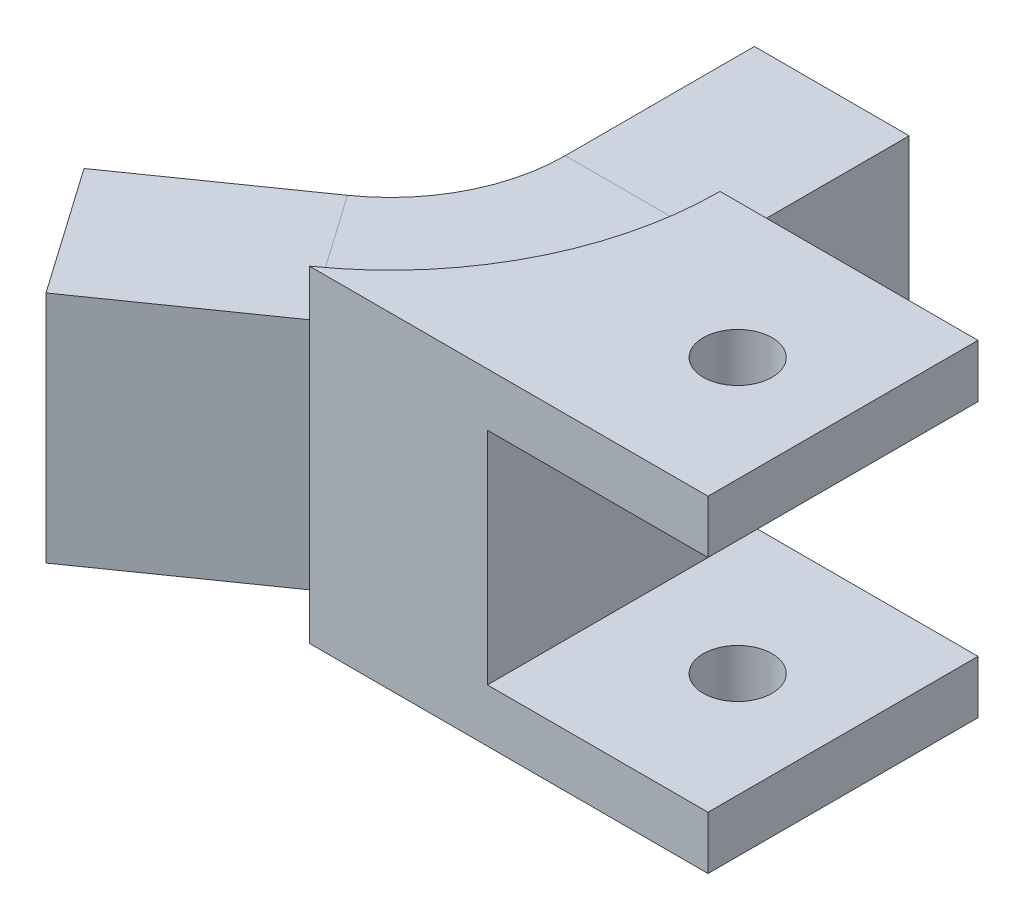
SolidWorks part; units mm, degrees
ref_plane "Front Plane" through (0, 0, 0) normal (0, 0, 1) x (1, 0, 0)
ref_plane "Top Plane" through (0, 0, 0) normal (0, 1, 0) x (1, 0, 0)
ref_plane "Right Plane" through (0, 0, 0) normal (1, 0, 0) x (0, 0, -1)
sketch "Sketch1" plane through (0, 0, 0) normal (0, 1, 0) x (1, 0, 0)
  line L0 (6.5349, -23.4717) -> (21.2796, -13.1473) construction
  line L1 (21.2796, -13.1473) -> (21.2796, 4.8527) construction
  line L2 (21.2796, 4.8527) -> (21.2796, 26.8527)
  line L3 (6.5349, -23.4717) -> (-11.4864, -36.0904)
  arc A0 (6.5349, -23.4717) -> (21.2796, 4.8527) centre (-13.298, 4.8527) ccw
  dimension "D1" = 125
  dimension "D2" = 18
ref_plane "Plane1" through (0, 0, -26.8527) normal (0, 0, 1) x (1, 0, 0)
sketch "Sketch5" plane through (0, 0, -26.8527) normal (0, 0, 1) x (1, 0, 0)
  line L0 (21.2796, 9.6) -> (21.2796, 0)
  line L1 (21.2796, -9.6) -> (7.0296, -9.6)
  line L3 (21.2796, 9.6) -> (7.0296, 9.6)
  line L4 (7.0296, 9.6) -> (7.0296, 13.6)
  line L5 (21.2796, 0) -> (21.2796, -9.6)
  line L6 (7.0296, 13.6) -> (25.0296, 13.6)
  line L7 (25.0296, 13.6) -> (25.0296, -13.6)
  line L8 (7.0296, -9.6) -> (7.0296, -13.6)
  line L9 (7.0296, -13.6) -> (25.0296, -13.6)
sweep "Sweep1" add profiles "Sketch5" path "Sketch1"
sketch "Sketch6" plane through (0, 0, -26.8527) normal (0, 0, -1) x (-1, 0, 0)
  line L0 (-21.2796, 0) -> (-6.3887, 0) construction
  line L1 (-7.0296, 9.6) -> (-10.0296, 8.1)
  line L2 (-10.0296, 8.1) -> (-10.0296, 9.6)
  line L3 (-7.0296, 9.6) -> (-21.2796, 9.6) construction
  line L4 (-7.0296, 9.6) -> (-10.0296, 9.6)
  line L5 (-7.0296, -9.6) -> (-10.0296, -8.1)
  line L6 (-10.0296, -8.1) -> (-10.0296, -9.6)
  line L7 (-7.0296, -9.6) -> (-10.0296, -9.6)
  dimension "D1" = 3
extrude "Boss-Extrude1" add sketch "Sketch6" against normal blind 15
sketch "Sketch7" plane through (-24.6644, 0, 17.2702) normal (-0.8192, 0, 0.5736) x (0.5736, 0, 0.8192)
  line L0 (8.7251, 9.6) -> (11.7251, 8.1)
  line L1 (11.7251, 8.1) -> (11.7251, 9.6)
  line L2 (8.7251, 9.6) -> (22.9751, 9.6) construction
  line L3 (11.7251, 9.6) -> (8.7251, 9.6)
  line L4 (22.9751, 0) -> (9.789, 0) construction
  line L5 (11.7251, -8.1) -> (11.7251, -9.6)
  line L6 (8.7251, -9.6) -> (11.7251, -8.1)
  line L7 (11.7251, -9.6) -> (8.7251, -9.6)
  dimension "D1" = 3
  dimension "D2" = 1.5
extrude "Boss-Extrude2" add sketch "Sketch7" against normal blind 15
ref_plane "Plane2" through (0, 0, 0) normal (0, 1, 0) x (1, 0, 0)
sketch "Sketch8" plane through (0, 13.6, 0) normal (0, 1, 0) x (1, 0, 0)
  line L0 (8.6858, -26.5435) -> (25.0296, -26.5435)
  line L2 (25.0296, -26.5435) -> (55.0296, -26.5435)
  line L3 (55.0296, -26.5435) -> (55.0296, 4.8527)
  line L4 (25.0296, 4.8527) -> (55.0296, 4.8527)
  arc A0 (8.6858, -26.5435) -> (25.0296, 4.8527) centre (-13.298, 4.8527) ccw construction
  arc A1 (8.6858, -26.5435) -> (25.0296, 4.8527) centre (-13.298, 4.8527) ccw
extrude "Boss-Extrude3" add sketch "Sketch8" against normal blind 19 and the other way blind 19 from surface at -13.6 starting at plane "Plane2"
sketch "Sketch9" plane through (0, 0, -4.8527) normal (0, 0, -1) x (-1, 0, 0)
  line L0 (-55.0296, -19) -> (-55.0296, 19) construction
  line L1 (-55.0296, -12.825) -> (-29.3796, -12.825)
  line L2 (-55.0296, -12.825) -> (-55.0296, 12.825)
  line L3 (-55.0296, 12.825) -> (-29.3796, 12.825)
  line L4 (-29.3796, -12.825) -> (-29.3796, 12.825)
  point P4 (-55.0296, 0)
  point P7 (-55.0296, 0)
  dimension "D1" = 25.65
extrude "Cut-Extrude2" cut sketch "Sketch9" against normal blind 41
sketch "Sketch10" plane through (0, -19, 0) normal (0, -1, 0) x (1, 0, 0)
  line L0 (55.0296, 10.8454) -> (42.7796, 10.8454) construction
  line L1 (55.0296, 26.5435) -> (55.0296, -4.8527) construction
  circle A0 centre (42.7796, 10.8454) radius 4
extrude "Cut-Extrude3" cut sketch "Sketch10" against normal blind 41
